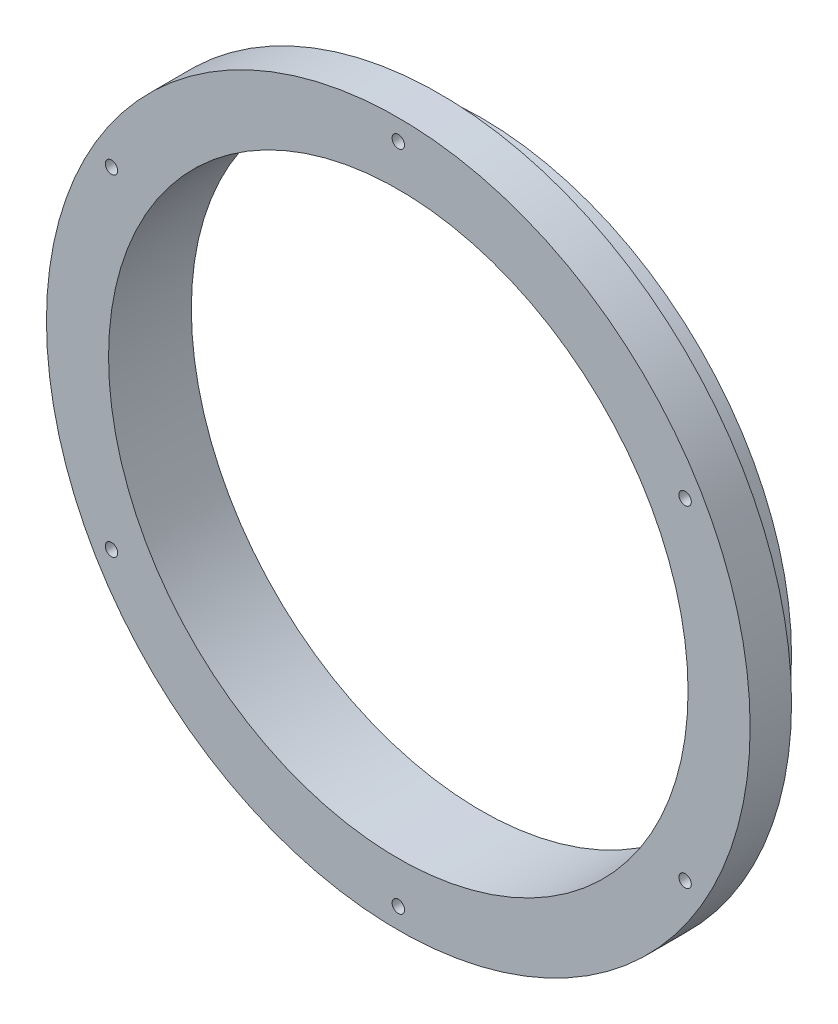
SolidWorks part; units mm, degrees
ref_plane "Ön Düzlem" through (0, 0, 0) normal (0, 0, 1) x (1, 0, 0)
ref_plane "Üst Düzlem" through (0, 0, 0) normal (0, 1, 0) x (1, 0, 0)
ref_plane "Sağ Düzlem" through (0, 0, 0) normal (1, 0, 0) x (0, 0, -1)
sketch "Sketch1" plane through (0, 0, 0) normal (0, 0, 1) x (1, 0, 0)
  circle A0 centre (0, 0) radius 85
  circle A1 centre (0, 0) radius 70
  dimension "D1" = 170
  dimension "D2" = 140
extrude "Boss-Extrude1" add sketch "Sketch1" along normal blind 10
sketch "Sketch2" plane through (0, 0, 0) normal (0, 0, 1) x (1, 0, 0)
  line L0 (0, 70) -> (0, -70) construction
  circle A0 centre (0, 0) radius 80 construction
  circle A1 centre (0, 80) radius 1.5
  circle A2 centre (0, 0) radius 70 construction
  dimension "D1" = 160
  dimension "D2" = 3
extrude "Cut-Extrude1" cut sketch "Sketch2" along normal blind 10
pattern_circular "CirPattern1" count 6 over 360 about axis through (0, 0, 0) along (0, 0, 1) of "Cut-Extrude1"
sketch "Sketch3" plane through (0, 0, 0) normal (0, 0, -1) x (-1, 0, 0)
  circle A0 centre (0, 0) radius 70
  circle A1 centre (0, 0) radius 75
  dimension "D1" = 150
  dimension "D2" = 140
extrude "Boss-Extrude2" add sketch "Sketch3" along normal blind 10
